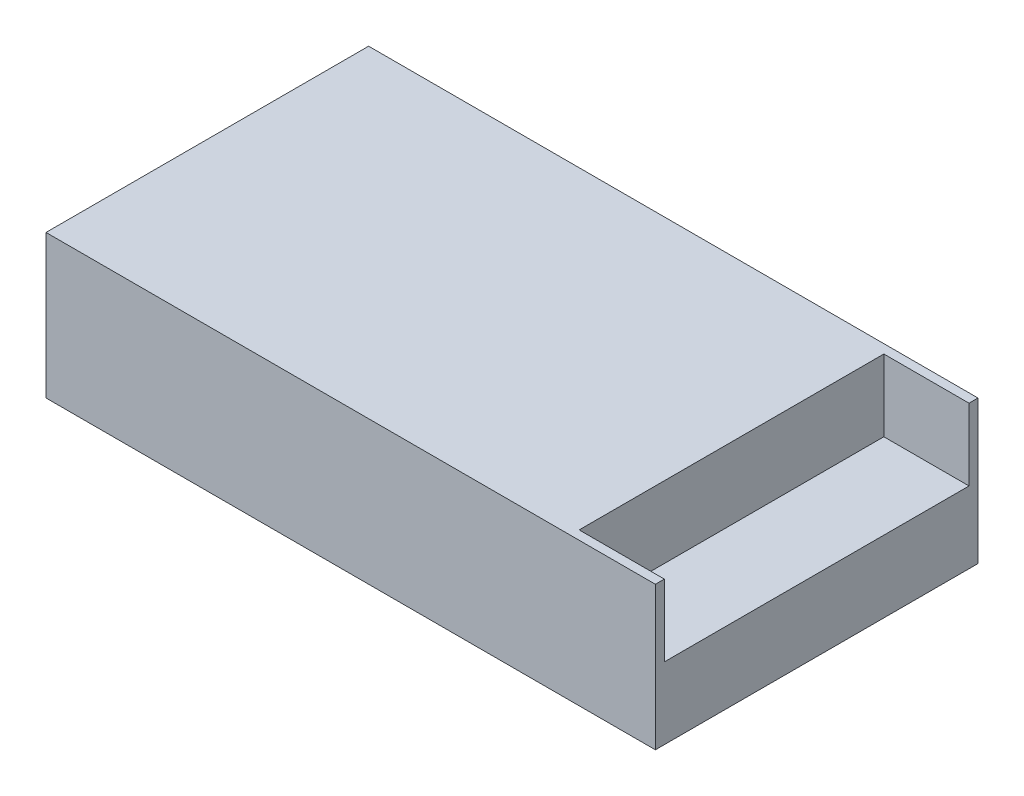
SolidWorks part; units mm, degrees
ref_plane "Front Plane" through (0, 0, 0) normal (0, 0, 1) x (1, 0, 0)
ref_plane "Top Plane" through (0, 0, 0) normal (0, 1, 0) x (1, 0, 0)
ref_plane "Right Plane" through (0, 0, 0) normal (1, 0, 0) x (0, 0, -1)
sketch "Sketch1" plane through (0, 0, 0) normal (0, 1, 0) x (1, 0, 0)
  line L1 (0, 0) -> (215.9, 0)
  line L2 (0, 0) -> (0, 114.3)
  line L3 (0, 114.3) -> (215.9, 114.3)
  line L4 (215.9, 0) -> (215.9, 114.3)
  dimension "D1" = 114.3
  dimension "D2" = 215.9
extrude "Boss-Extrude1" add sketch "Sketch1" along normal blind 50.8
sketch "Sketch2" plane through (0, 50.8, 0) normal (0, 1, 0) x (1, 0, 0)
  line L0 (215.9, 0) -> (215.9, 114.3) construction
  line L1 (215.9, 111.125) -> (185.7189, 111.125)
  line L2 (215.9, 111.125) -> (215.9, 3.175)
  line L3 (215.9, 3.175) -> (185.7189, 3.175)
  line L4 (185.7189, 111.125) -> (185.7189, 3.175)
  line L5 (215.9, 114.3) -> (0, 114.3) construction
  line L6 (0, 0) -> (215.9, 0) construction
  dimension "D1" = 3.175
  dimension "D2" = 3.175
extrude "Cut-Extrude1" cut sketch "Sketch2" against normal blind 25.4
